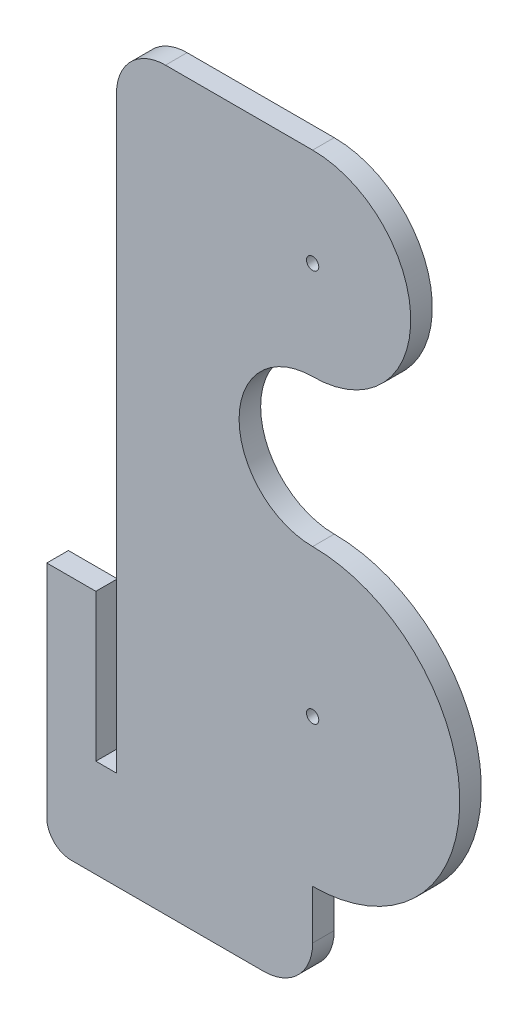
SolidWorks part; units mm, degrees
ref_plane "Front Plane" through (0, 0, 0) normal (0, 0, 1) x (1, 0, 0)
ref_plane "Top Plane" through (0, 0, 0) normal (0, 1, 0) x (1, 0, 0)
ref_plane "Right Plane" through (0, 0, 0) normal (1, 0, 0) x (0, 0, -1)
sketch "Sketch1" plane through (0, 0, 0) normal (0, 0, 1) x (1, 0, 0)
  line L0 (-15.2371, 13.2698) -> (-8.8871, 13.2698)
  line L2 (-15.2371, -18.4802) -> (-15.2371, 13.2698)
  line L4 (19.1799, -18.4802) -> (-15.2371, -18.4802)
  line L5 (-6.2201, 32.313) -> (-6.2201, 76.7698)
  line L6 (-6.2201, 76.7698) -> (19.1799, 76.7698)
  line L8 (-8.8871, 13.2698) -> (-8.8871, -5.7802)
  line L9 (-8.8871, -5.7802) -> (-6.2201, -5.7802)
  line L10 (-6.2201, 32.313) -> (-6.2201, -5.7802)
  line L16 (19.1799, -5.7802) -> (19.1799, -18.4802)
  arc A0 (19.1799, -5.7802) -> (19.1799, 32.3198) centre (19.1799, 13.2698) ccw
  circle A2 centre (19.1799, 13.2698) radius 0.7937
  arc A6 (19.1799, 76.7698) -> (19.1799, 51.3698) centre (19.1799, 64.0698) cw
  circle A7 centre (19.1799, 64.0698) radius 0.7937
  arc A8 (19.1799, 32.3198) -> (19.1799, 51.3698) centre (19.1799, 41.8448) cw
  point P0 (0, 0)
  point P6 (19.1799, 51.3698)
  point P24 (19.1799, 13.2698)
  dimension "D17" = 12.7
  dimension "D10" = 19.05
  dimension "D3" = 2.667
  dimension "D4" = 6.35
  dimension "D8" = 12.7
  dimension "D9" = 25.4
  dimension "D11" = 12.7
  dimension "D12" = 19.05
  dimension "D15" = 25.4
  dimension "D16" = 19.05
extrude "Boss-Extrude1" add sketch "Sketch1" along normal blind 2.794
fillet "Fillet1" radius 6.35 2 edges at (19.1799, -18.4802, 1.397) (-6.2201, 76.7698, 1.397)
fillet "Fillet2" radius 3.175 1 edges at (-15.2371, -18.4802, 1.397)
